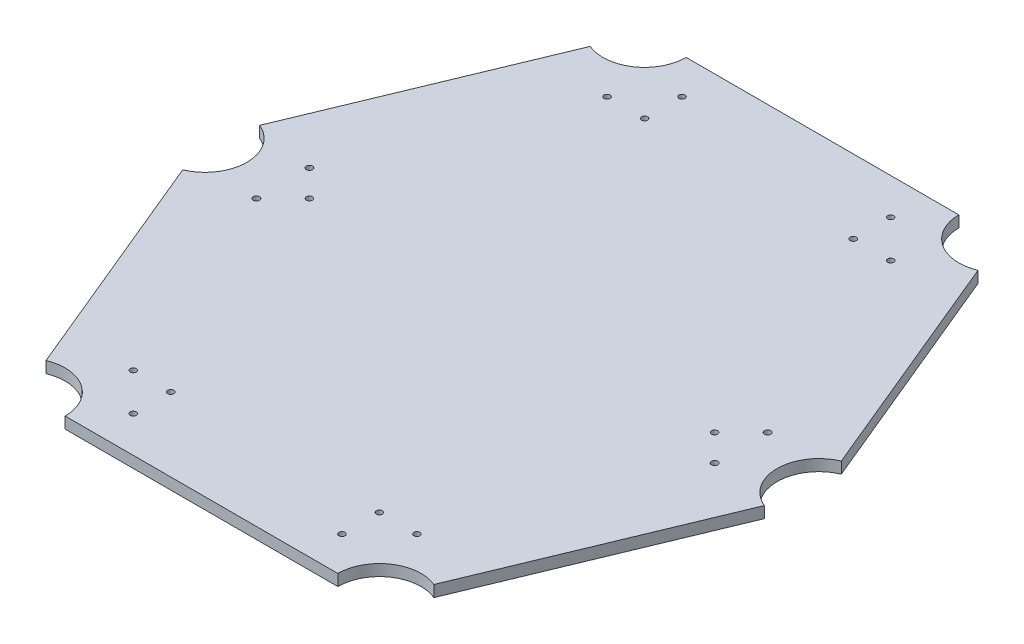
SolidWorks part; units mm, degrees
ref_plane "前视基准面" through (0, 0, 0) normal (0, 0, 1) x (1, 0, 0)
ref_plane "上视基准面" through (0, 0, 0) normal (0, 1, 0) x (1, 0, 0)
ref_plane "右视基准面" through (0, 0, 0) normal (1, 0, 0) x (0, 0, -1)
other "Configuration Table"
sketch "草图4" plane through (0, 0, 0) normal (0, 1, 0) x (1, 0, 0)
  line L0 (0, 0) -> (50.254, 0) construction
  line L1 (0, 0) -> (0, 95.6732) construction
  line L2 (-47, 82) -> (47, 82)
  line L3 (-47, 82) -> (-81, 0)
  line L4 (47, 82) -> (81, 0)
  line L5 (47, -82) -> (81, 0)
  line L6 (-47, -82) -> (47, -82)
  line L7 (-47, -82) -> (-81, 0)
  dimension "D1" = 94
  dimension "D2" = 94
  dimension "D3" = 82
  dimension "D4" = 162
extrude "凸台-拉伸1" add sketch "草图4" along normal blind 3
sketch "草图7" plane through (0, 3, 0) normal (0, 1, 0) x (1, 0, 0)
  circle A0 centre (-81, 0) radius 11
  circle A1 centre (-47, 82) radius 11
  circle A2 centre (47, 82) radius 11
  circle A3 centre (81, 0) radius 11
  circle A4 centre (47, -82) radius 11
  circle A5 centre (-47, -82) radius 11
  dimension "D1" = 22
extrude "切除-拉伸4" cut sketch "草图7" against normal through all
sketch "草图9" plane through (0, 3, 0) normal (0, 1, 0) x (1, 0, 0)
  line L0 (-47, 82) -> (-25.9637, 60.9637) construction
  line L1 (36, 82) -> (-36, 82) construction
  line L2 (-47, -82) -> (-8.0935, -43.0935) construction
  line L3 (-36, -82) -> (36, -82) construction
  line L4 (-81, 0) -> (-24.432, 0) construction
  line L5 (-27.5546, -62.5546) -> (-7.3369, -82.7722) construction
  line L6 (-27.5546, 62.5546) -> (-3.7699, 86.3392) construction
  circle A0 centre (-53.5, 0) radius 0.8
  circle A1 centre (-60.5, 7) radius 0.8253
  circle A2 centre (-60.5, -7) radius 0.8253
  circle A3 centre (-27.5546, -62.5546) radius 0.8
  circle A4 centre (-37.4541, -62.5546) radius 0.8
  circle A5 centre (-27.5546, -72.4541) radius 0.8
  circle A6 centre (-27.5546, 62.5546) radius 0.8
  circle A7 centre (-27.5546, 72.4541) radius 0.8
  circle A8 centre (-37.4541, 62.5546) radius 0.8
  dimension "D3" = 1.6
  dimension "D4" = 27.5
  dimension "D6" = 7
  dimension "D7" = 270
  dimension "D10" = 1.6
  dimension "D12" = 27.5
  dimension "D14" = 1.6
  dimension "D15" = 7
  dimension "D1" = 45
  dimension "D2" = 45
  dimension "D5" = 7
  dimension "D8" = 7
  dimension "D9" = 7
  dimension "D11" = 27.5
  dimension "D13" = 7
extrude "切除-拉伸5" cut sketch "草图9" against normal through all
mirror "镜向2" about plane through (0, 0, 0) normal (1, 0, 0) of "切除-拉伸5"
